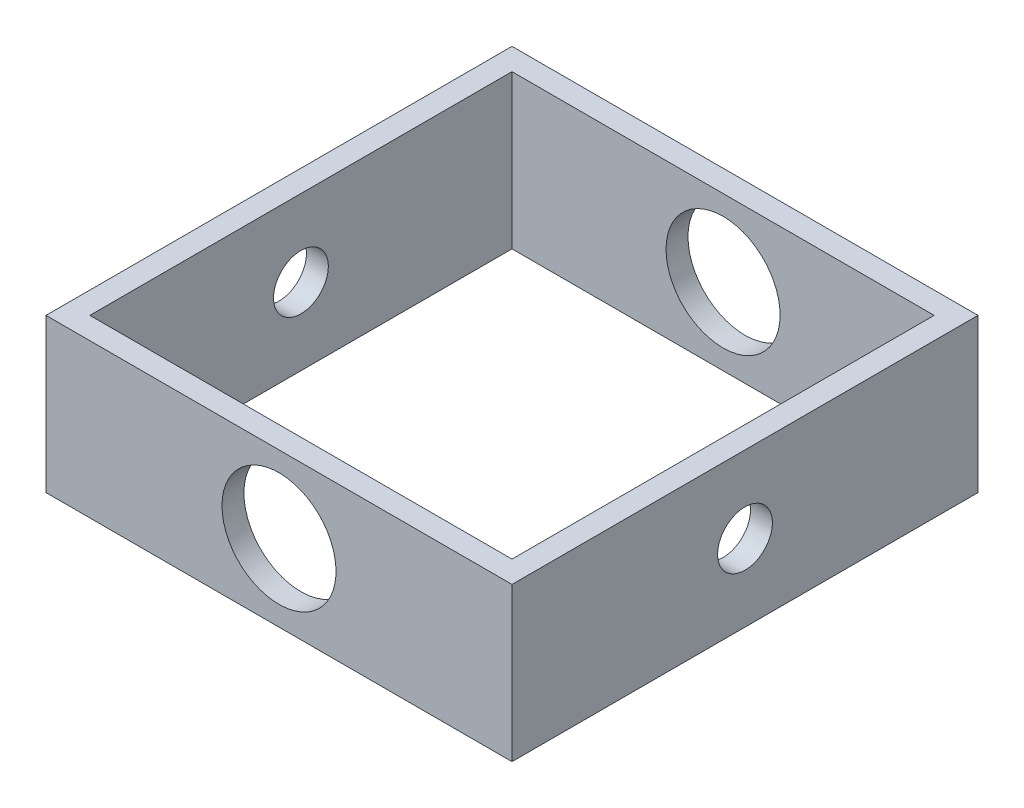
SolidWorks part; units mm, degrees
ref_plane "Front Plane" through (0, 0, 0) normal (0, 0, 1) x (1, 0, 0)
ref_plane "Top Plane" through (0, 0, 0) normal (0, 1, 0) x (1, 0, 0)
ref_plane "Right Plane" through (0, 0, 0) normal (1, 0, 0) x (0, 0, -1)
sketch "Sketch1" plane through (0, 0, 0) normal (0, 1, 0) x (1, 0, 0)
  line L1 (-12.2238, 12.2237) -> (12.2237, 12.2237)
  line L2 (-12.2238, 12.2237) -> (-12.2237, -12.2238)
  line L3 (-12.2237, -12.2238) -> (12.2237, -12.2238)
  line L4 (12.2237, 12.2237) -> (12.2237, -12.2238)
  line L5 (-12.2238, 12.2237) -> (12.2237, -12.2238) construction
  line L6 (-12.2237, -12.2238) -> (12.2237, 12.2237) construction
  line L7 (-13.4938, 13.4938) -> (13.4937, 13.4938)
  line L8 (-13.4938, 13.4938) -> (-13.4937, -13.4937)
  line L9 (-13.4937, -13.4937) -> (13.4937, -13.4937)
  line L10 (13.4937, 13.4938) -> (13.4937, -13.4937)
  line L11 (-13.4938, 13.4938) -> (13.4937, -13.4937) construction
  line L12 (-13.4937, -13.4937) -> (13.4937, 13.4938) construction
  point P0 (0, 0)
  point P6 (0, 0)
extrude "Boss-Extrude1" add sketch "Sketch1" along normal blind 8.89
sketch "Sketch2" plane through (13.4937, 0, 0) normal (1, 0, 0) x (0, 0, -1)
  circle A0 centre (0, 4.445) radius 1.5875
extrude "Cut-Extrude1" cut sketch "Sketch2" against normal blind 152.4
sketch "Sketch3" plane through (0, 0, -13.4938) normal (0, 0, -1) x (-1, 0, 0)
  circle A0 centre (0, 4.445) radius 3.302
extrude "Cut-Extrude3" cut sketch "Sketch3" against normal blind 152.4
